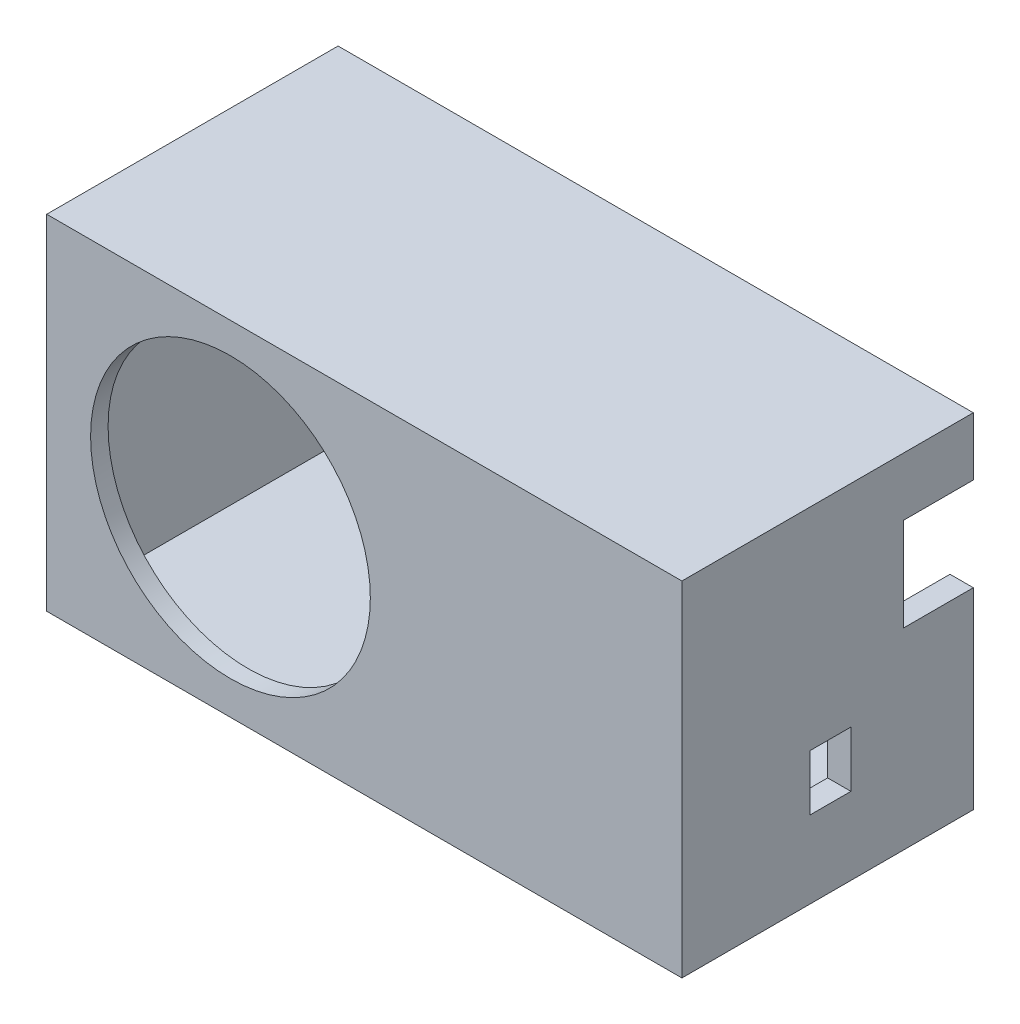
SolidWorks part; units mm, degrees
ref_plane "Plan de face" through (0, 0, 0) normal (0, 0, 1) x (1, 0, 0)
ref_plane "Plan de dessus" through (0, 0, 0) normal (0, 1, 0) x (1, 0, 0)
ref_plane "Plan de droite" through (0, 0, 0) normal (1, 0, 0) x (0, 0, -1)
sketch "Esquisse1" plane through (0, 0, 0) normal (0, 0, 1) x (1, 0, 0)
  line L0 (-88.3067, 0) -> (20.6933, 0)
  line L1 (20.6933, 0) -> (20.6933, -59)
  line L2 (-88.3067, 0) -> (-88.3067, -59)
  line L3 (-88.3067, -59) -> (20.6933, -59)
extrude "Boss.-Extru.1" add sketch "Esquisse1" along normal blind 50
sketch "Esquisse2" plane through (0, 0, 0) normal (0, 0, 1) x (1, 0, 0)
  line L11 (-84.3067, -55) -> (16.6933, -55)
  line L12 (16.6933, -55) -> (16.6933, -4)
  line L13 (-84.3067, -4) -> (16.6933, -4)
  line L14 (-84.3067, -55) -> (-84.3067, -4)
extrude "Enlèv. mat.-Extru.1" cut sketch "Esquisse2" along normal blind 47
sketch "Esquisse3" plane through (0, 0, 0) normal (1, 0, 0) x (0, 0, -1)
  line L0 (-28, -36.2033) -> (-28, -45.7629)
  line L2 (-28, -45.7629) -> (-21, -45.7629)
  line L3 (-21, -45.7629) -> (-21, -36.2033)
  line L4 (-21, -36.2033) -> (-28, -36.2033)
  line L5 (0, -59) -> (0, 0) construction
  line L6 (0, -10) -> (-12, -10)
  line L7 (-12, -10) -> (-12, -26)
  line L8 (-12, -26) -> (0, -26)
  line L9 (0, -26) -> (0, -10)
extrude "Enlèv. mat.-Extru.2" cut sketch "Esquisse3" along normal through all and the other way blind 21
sketch "Esquisse4" plane through (0, 0, 0) normal (0, 0, 1) x (1, 0, 0)
  line L0 (-93.5539, -29.2504) -> (25.6077, -29.2504) construction
  circle A1 centre (-56.7736, -29.2504) radius 24
extrude "Enlèv. mat.-Extru.3" cut sketch "Esquisse4" along normal blind 73
